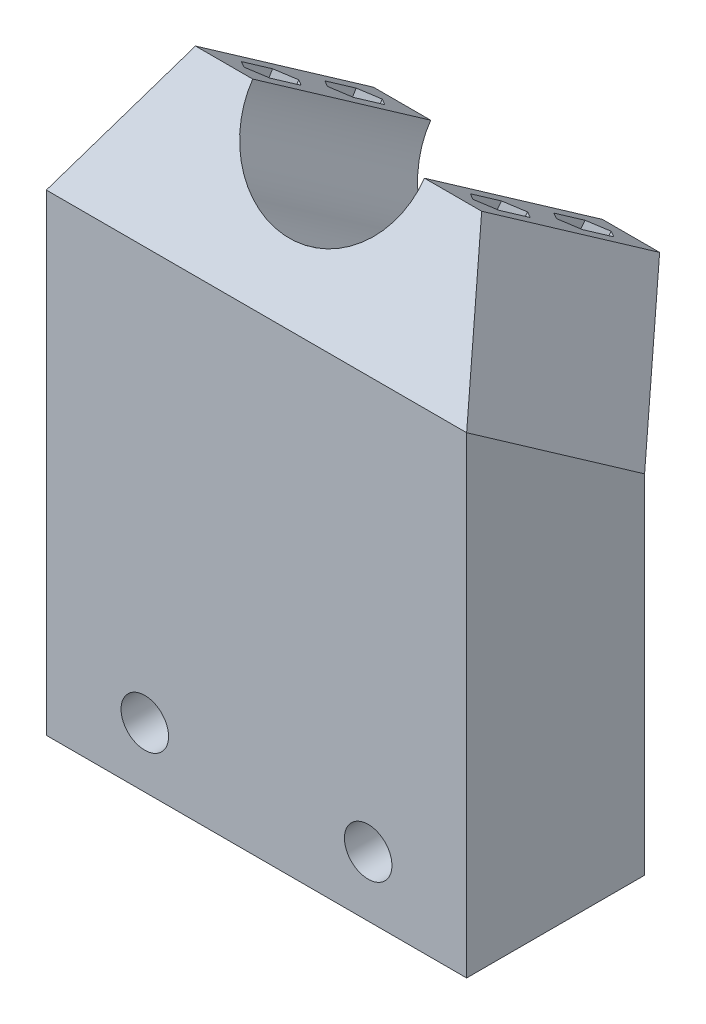
SolidWorks part; units mm, degrees
ref_plane "Alzado" through (0, 0, 0) normal (0, 0, 1) x (1, 0, 0)
ref_plane "Planta" through (0, 0, 0) normal (0, 1, 0) x (1, 0, 0)
ref_plane "Vista lateral" through (0, 0, 0) normal (1, 0, 0) x (0, 0, -1)
sketch "Croquis1" plane through (0, 0, 0) normal (0, 0, 1) x (1, 0, 0)
  line L0 (22.0266, 0) -> (22.0266, 6.2992) construction
  line L1 (0, 0) -> (44.0531, 0)
  line L2 (0, 0) -> (0, 36.4389)
  line L3 (0, 36.4389) -> (44.0531, 36.4389)
  line L4 (44.0531, 0) -> (44.0531, 36.4389)
  circle A0 centre (10.3187, 6.2992) radius 2.4892
  circle A1 centre (33.7344, 6.2992) radius 2.4892
  dimension "D1" = 4.9784
  dimension "D2" = 10.3187
  dimension "D3" = 3.81
  dimension "D4" = 32.6289
  dimension "D5" = 44.0531
extrude "Saliente-Extruir1" add sketch "Croquis1" along normal blind 18.6531
sketch "Croquis3" plane through (0, 0, 0) normal (-1, 0, 0) x (0, 0, 1)
  line L0 (0, 36.4389) -> (18.6531, 49.4999)
  line L1 (0, 36.4389) -> (-7.8285, 47.6192) construction
  line L2 (18.6531, 49.4999) -> (18.6531, 36.4389)
  line L3 (0, 36.4389) -> (18.6531, 36.4389)
  dimension "D1" = 35
ref_plane "Plano2" through (0, 11.988, 17.1207) normal (0, 0.5736, 0.8192) x (1, 0, 0)
extrude "Saliente-Extruir2" add sketch "Croquis3" against normal up to vertex (44.0531 mm away)
sketch "Croquis5" plane through (0, 11.988, 17.1207) normal (0, 0.5736, 0.8192) x (1, 0, 0)
  line L0 (22.0266, 29.849) -> (22.0266, 44.849) construction
  line L1 (44.0531, 29.849) -> (0, 29.849) construction
  line L2 (7.0266, 44.849) -> (13.0266, 44.849)
  line L3 (13.0266, 44.849) -> (31.0266, 44.849)
  line L4 (31.0266, 44.849) -> (37.0266, 44.849)
  line L5 (7.0266, 44.849) -> (0, 29.849)
  line L6 (0, 29.849) -> (44.0531, 29.849)
  line L7 (44.0531, 29.849) -> (37.0266, 44.849)
  circle A0 centre (22.0266, 44.849) radius 15
  circle A1 centre (22.0266, 44.849) radius 9
  dimension "D1" = 18
  dimension "D2" = 6
extrude "Saliente-Extruir3" add sketch "Croquis5" along normal up to vertex (22.7713 mm away) separate body contours A0 L0 A1 L2 | L0 A0 L4 A1 | A0 L5 L6 | A0 L6 L7
sketch "Croquis7" plane through (0, 36.7381, -25.7243) normal (0, 0.8192, -0.5736) x (1, 0, 0)
  line L0 (10.0266, -20.9005) -> (10.0266, -23.4405) construction
  line L1 (8.5266, -28.9405) -> (8.5266, -24.9405)
  line L2 (11.5266, -28.9405) -> (11.5266, -24.9405)
  line L3 (8.5266, -28.9405) -> (10.0266, -30.4405)
  line L4 (10.0266, -30.4405) -> (11.5266, -28.9405)
  line L5 (11.5266, -24.9405) -> (10.0266, -23.4405)
  line L6 (10.0266, -23.4405) -> (8.5266, -24.9405)
  line L7 (7.0266, -20.9005) -> (13.0266, -20.9005) construction
  line L8 (7.0266, -32.2861) -> (11.7793, -32.2861) construction
  line L9 (7.0266, -43.6717) -> (7.0266, -20.9005) construction
  line L10 (10.0266, -41.1317) -> (8.5266, -39.6317)
  line L11 (11.5266, -39.6317) -> (10.0266, -41.1317)
  line L12 (10.0266, -34.1317) -> (11.5266, -35.6317)
  line L13 (8.5266, -35.6317) -> (10.0266, -34.1317)
  line L14 (11.5266, -35.6317) -> (11.5266, -39.6317)
  line L15 (8.5266, -35.6317) -> (8.5266, -39.6317)
  line L16 (13.0266, -43.6717) -> (31.0266, -43.6717) construction
  line L17 (13.0266, -43.6717) -> (31.0266, -43.6717) construction
  line L18 (22.0266, -43.6717) -> (22.0266, -38.4515) construction
  point P2 (11.3797, -24.6032)
  point P10 (11.3797, -39.969)
  dimension "D1" = 4
  dimension "D2" = 3
  dimension "D3" = 2.54
revolve "Cortar-Revolución1" cut sketch "Croquis7" angle 360 about L18
